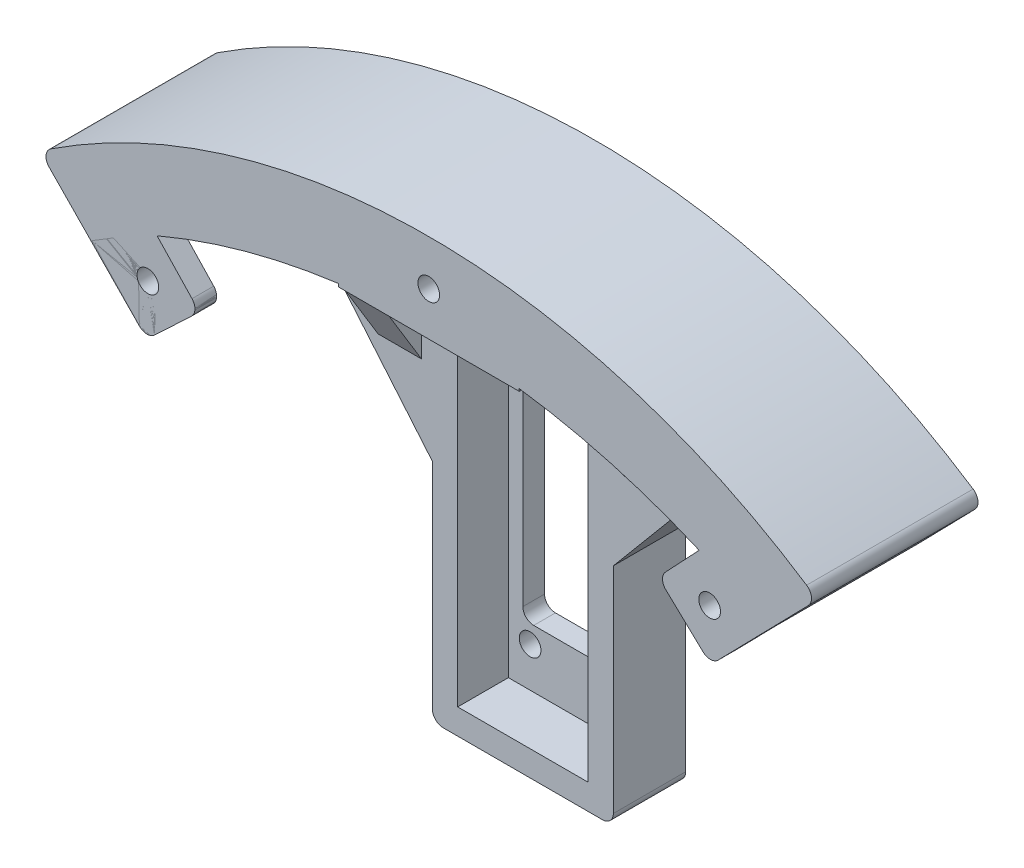
SolidWorks part; units mm, degrees
material "ABS"
ref_plane "Alzado" through (0, 0, 0) normal (0, 0, 1) x (1, 0, 0)
ref_plane "Planta" through (0, 0, 0) normal (0, 1, 0) x (1, 0, 0)
ref_plane "Vista lateral" through (0, 0, 0) normal (1, 0, 0) x (0, 0, -1)
sketch "Croquis1" plane through (0, 0, 0) normal (0, 0, 1) x (1, 0, 0)
  circle A0 centre (0, 0) radius 100
  dimension "D1" = 200
extrude "Saliente-Extruir1" add sketch "Croquis1" along normal blind 3
sketch "Croquis3" plane through (0, 0, 3) normal (0, 0, 1) x (1, 0, 0)
  line L0 (0, 0) -> (190, 0) construction
  circle A0 centre (190, 0) radius 110
  dimension "D1" = 220
  dimension "D2" = 190
extrude "Cortar-Extruir1" cut sketch "Croquis3" against normal blind 3
fillet "Redondeo1" radius 10 2 edges at (89.4737, -44.6594, 1.5) (89.4737, 44.6594, 1.5)
sketch "Croquis5" plane through (0, 0, 3) normal (0, 0, 1) x (1, 0, 0)
  line L0 (0, -100) -> (0, 100) construction
  line L1 (-100, 0) -> (80, 0) construction
  line L2 (0, 0) -> (-70.7107, -70.7107) construction
  line L3 (-70.7107, -70.7107) -> (70.7107, 70.7107) construction
  line L4 (0, 0) -> (-70.7107, 70.7107) construction
  line L5 (-70.7107, 70.7107) -> (70.7107, -70.7107) construction
  line L6 (-70.7107, -70.7107) -> (-58.3363, -83.085) construction
  line L9 (-58.3363, -83.085) -> (-83.085, -58.3363)
  line L11 (-83.085, -58.3363) -> (-65.4074, -40.6586)
  line L12 (-65.4074, -40.6586) -> (-40.6586, -65.4074)
  line L13 (-40.6586, -65.4074) -> (-58.3363, -83.085)
  line L14 (-70.7107, 70.7107) -> (-83.085, 58.3363) construction
  line L15 (-83.085, 58.3363) -> (-100, 0) construction
  line L17 (-83.085, 58.3363) -> (-58.3363, 83.085)
  line L18 (-58.3363, 83.085) -> (-40.6586, 65.4074)
  line L19 (-40.6586, 65.4074) -> (-65.4074, 40.6586)
  line L20 (-65.4074, 40.6586) -> (-83.085, 58.3363)
  line L22 (70.7107, -70.7107) -> (58.3363, -83.085) construction
  line L23 (58.3363, -83.085) -> (0, -100) construction
  line L24 (58.3363, -83.085) -> (83.085, -58.3363)
  line L25 (83.085, -58.3363) -> (65.4074, -40.6586)
  line L26 (65.4074, -40.6586) -> (40.6586, -65.4074)
  line L27 (40.6586, -65.4074) -> (58.3363, -83.085)
  line L28 (70.7107, 70.7107) -> (58.3363, 83.085) construction
  line L29 (58.3363, 83.085) -> (0, 100) construction
  line L30 (58.3363, 83.085) -> (83.085, 58.3363)
  line L31 (83.085, 58.3363) -> (65.4074, 40.6586)
  line L32 (65.4074, 40.6586) -> (40.6586, 65.4074)
  line L33 (40.6586, 65.4074) -> (58.3363, 83.085)
  arc A0 (87.1345, 49.0671) -> (87.1345, -49.0671) centre (0, 0) ccw construction
  arc A1 (87.7193, 40.4803) -> (87.7193, -40.4803) centre (190, 0) ccw construction
  point P36 (0, 0)
  dimension "D2" = 17.5
  dimension "D3" = 25
  dimension "D4" = 35
  dimension "D5" = 25
  dimension "D6" = 35
  dimension "D8" = 25
  dimension "D9" = 17.5
  dimension "D7" = 35
  dimension "D10" = 90
  dimension "D11" = 17.5
  dimension "D12" = 17.5
  dimension "D13" = 35
  dimension "D14" = 25
  dimension "D15" = 134.3503
  dimension "D16" = 100
extrude "Cortar-Extruir6" cut sketch "Croquis5" against normal blind 10
sketch "Croquis12" plane through (0, 0, 3) normal (0, 0, 1) x (1, 0, 0)
  line L0 (-53.033, -53.033) -> (-39.9421, -50.0116) construction
  line L1 (-40.6586, -65.4074) -> (-65.4074, -40.6586) construction
  line L2 (-39.9421, -50.0116) -> (-36.8049, -63.6043) construction
  line L3 (-36.8049, -63.6043) -> (-63.6043, -36.8049) construction
  line L4 (-63.6043, -36.8049) -> (-47.6661, -20.8667) construction
  line L6 (53.033, -53.033) -> (-53.033, 53.033) construction
  line L7 (65.4074, -40.6586) -> (40.6586, -65.4074) construction
  line L8 (-65.4074, 40.6586) -> (-40.6586, 65.4074) construction
  line L9 (36.8049, 63.6043) -> (20.8667, 47.6661) construction
  line L10 (63.6043, 36.8049) -> (36.8049, 63.6043) construction
  line L11 (50.0116, 39.9421) -> (63.6043, 36.8049) construction
  line L12 (53.033, 53.033) -> (50.0116, 39.9421) construction
  line L14 (53.033, -53.033) -> (50.2046, -50.2046) construction
  line L15 (50.2046, -50.2046) -> (36.8049, -63.6043) construction
  line L16 (36.8049, -63.6043) -> (63.6043, -36.8049) construction
  line L17 (63.6043, -36.8049) -> (47.6661, -20.8667) construction
  line L19 (-53.033, -53.033) -> (53.033, 53.033) construction
  line L20 (-36.8049, 63.6043) -> (-20.8667, 47.6661) construction
  line L21 (-63.6043, 36.8049) -> (-36.8049, 63.6043) construction
  line L22 (-50.2046, 50.2046) -> (-63.6043, 36.8049) construction
  line L23 (-53.033, 53.033) -> (-50.2046, 50.2046) construction
  circle A0 centre (-63.6043, -36.8049) radius 1.5
  circle A1 centre (-36.8049, -63.6043) radius 1.5
  circle A2 centre (-47.6661, -20.8667) radius 1.5
  circle A3 centre (-20.8667, -47.6661) radius 1.5
  circle A5 centre (47.6661, 20.8667) radius 1.5
  circle A6 centre (20.8667, 47.6661) radius 1.5
  circle A7 centre (63.6043, 36.8049) radius 1.5
  circle A8 centre (36.8049, 63.6043) radius 1.5
  circle A10 centre (20.8667, -47.6661) radius 1.5
  circle A11 centre (47.6661, -20.8667) radius 1.5
  circle A12 centre (63.6043, -36.8049) radius 1.5
  circle A13 centre (36.8049, -63.6043) radius 1.5
  circle A15 centre (-63.6043, 36.8049) radius 1.5
  circle A16 centre (-36.8049, 63.6043) radius 1.5
  circle A17 centre (-20.8667, 47.6661) radius 1.5
  circle A18 centre (-47.6661, 20.8667) radius 1.5
  dimension "D2" = 3
  dimension "D3" = 3
  dimension "D4" = 4
  dimension "D5" = 4
  dimension "D6" = 3
  dimension "D7" = 3
  dimension "D8" = 37.9
  dimension "D9" = 22.54
  dimension "D10" = 22.54
  dimension "D11" = 37.9
  dimension "D12" = 18.95
  dimension "D13" = 18.95
  dimension "D14" = 3
  dimension "D15" = 3
  dimension "D16" = 3
  dimension "D17" = 3
  dimension "D18" = 37.9
  dimension "D19" = 22.54
  dimension "D20" = 22.54
  dimension "D21" = 37.9
  dimension "D22" = 4
  dimension "D1" = 13.95
extrude "Cortar-Extruir7" cut sketch "Croquis12" against normal through all
sketch "Croquis9" plane through (0, 0, 3) normal (0, 0, 1) x (1, 0, 0)
  line L0 (0, 0) -> (-100, 0) construction
  line L5 (0, 100) -> (0, -100) construction
  line L6 (38.9591, 4) -> (43.4591, 4)
  line L7 (38.9591, 4) -> (38.9591, -4)
  line L8 (38.9591, -4) -> (43.4591, -4)
  line L9 (43.4591, 4) -> (43.4591, -4)
  line L10 (-4, -52) -> (4, -52)
  line L11 (-58.1901, 4) -> (-62.6901, 4)
  line L12 (-58.1901, 4) -> (-58.1901, -4)
  line L13 (-58.1901, -4) -> (-62.6901, -4)
  line L14 (-62.6901, 4) -> (-62.6901, -4)
  line L15 (-4, 56.5) -> (4, 56.5)
  line L16 (-4, 56.5) -> (-4, 52)
  line L17 (-4, 52) -> (4, 52)
  line L18 (4, 56.5) -> (4, 52)
  line L19 (4, -56.5) -> (4, -52)
  line L20 (-4, -56.5) -> (4, -56.5)
  line L21 (-4, -56.5) -> (-4, -52)
  line L22 (0, 0) -> (80, 0) construction
  line L24 (-58.2511, -4) -> (-58.2738, -4) construction
  circle A0 centre (71.9, -4) radius 1.5
  circle A1 centre (35.9591, 4) radius 1.5
  circle A4 centre (71.9591, 4) radius 1.5
  circle A5 centre (35.9, -4) radius 1.5
  arc A6 (-81.9939, 57.2451) -> (-81.9939, -57.2451) centre (0, 0) ccw construction
  arc A7 (87.7193, 40.4803) -> (87.7193, -40.4803) centre (190, 0) ccw construction
  circle A8 centre (-91.1901, 4) radius 1.5
  circle A9 centre (-91.1901, -4) radius 1.5
  circle A10 centre (-55.1901, 4) radius 1.5
  circle A11 centre (-55.1901, -4) radius 1.5
  circle A12 centre (-4, 85) radius 1.5
  circle A13 centre (4, 85) radius 1.5
  circle A14 centre (-4, 49) radius 1.5
  circle A15 centre (4, 49) radius 1.5
  circle A20 centre (-4, -49) radius 1.5
  circle A21 centre (4, -49) radius 1.5
  circle A22 centre (4, -85) radius 1.5
  circle A23 centre (-4, -85) radius 1.5
  arc A24 (87.1345, 49.0671) -> (81.9939, 57.2451) centre (0, 0) ccw construction
  arc A25 (57.2451, 81.9939) -> (-57.2451, 81.9939) centre (0, 0) ccw construction
  dimension "D6" = 35.9
  dimension "D7" = 3
  dimension "D8" = 36
  dimension "D9" = 36
  dimension "D10" = 3
  dimension "D11" = 3
  dimension "D12" = 4
  dimension "D13" = 4
  dimension "D14" = 3
  dimension "D15" = 3
  dimension "D16" = 3
  dimension "D21" = 4
  dimension "D22" = 4
  dimension "D23" = 3
  dimension "D24" = 3
  dimension "D25" = 4
  dimension "D26" = 4
  dimension "D27" = 36
  dimension "D28" = 36
  dimension "D29" = 91.1901
  dimension "D30" = 91.1901
  dimension "D35" = 3
  dimension "D36" = 3
  dimension "D37" = 8
  dimension "D38" = 4
  dimension "D39" = 3
  dimension "D40" = 3
  dimension "D41" = 8
  dimension "D42" = 36
  dimension "D43" = 36
  dimension "D44" = 36
  dimension "D45" = 4
  dimension "D46" = 4
  dimension "D51" = 4
  dimension "D52" = 4
  dimension "D53" = 36.1809
  dimension "D55" = 36
  dimension "D56" = 49
  dimension "D57" = 49
  dimension "D58" = 3
  dimension "D59" = 3
  dimension "D60" = 3
  dimension "D61" = 3
  dimension "D62" = 4.5
  dimension "D32" = 8
  dimension "D64" = 0
  dimension "D69" = 8
  dimension "D70" = 4
  dimension "D71" = 85.0941
  dimension "D72" = 85.0941
  dimension "D17" = 4.5
  dimension "D18" = 8
  dimension "D19" = 3
  dimension "D20" = 0
  dimension "D31" = 3.061
  dimension "D33" = 3
  dimension "D34" = 0
  dimension "D47" = 8
  dimension "D48" = 4.5
  dimension "D49" = 0
  dimension "D50" = 3
  dimension "D54" = 4
  dimension "D63" = 0
  dimension "D65" = 3
  dimension "D66" = 4.5
  dimension "D67" = 8
  dimension "D68" = 3
extrude "Cortar-Extruir5" cut sketch "Croquis9" against normal blind 10
sketch "Croquis13" plane through (0, 0, 3) normal (0, 0, 1) x (1, 0, 0)
  line L0 (-57.2451, 81.9939) -> (-46.4963, 71.2451) construction
  line L1 (-40.6586, 65.4074) -> (-57.2451, 81.9939) construction
  line L2 (57.2451, 81.9939) -> (46.2825, 71.0313) construction
  line L3 (57.2451, 81.9939) -> (40.6586, 65.4074) construction
  line L4 (0, 100) -> (0, 95) construction
  line L5 (-46.4963, 71.2451) -> (-40.6586, 65.4074)
  line L6 (-40.6586, 65.4074) -> (-65.4074, 40.6586)
  line L7 (-65.4074, 40.6586) -> (-81.9939, 57.2451)
  line L8 (-81.9939, -57.2451) -> (-65.4074, -40.6586)
  line L9 (-65.4074, -40.6586) -> (-40.6586, -65.4074)
  line L10 (-40.6586, -65.4074) -> (-57.2451, -81.9939)
  line L12 (81.9939, -57.2451) -> (65.4074, -40.6586)
  line L13 (65.4074, -40.6586) -> (40.6586, -65.4074)
  line L14 (40.6586, -65.4074) -> (57.2451, -81.9939)
  line L15 (46.2825, 71.0313) -> (40.6586, 65.4074)
  line L16 (40.6586, 65.4074) -> (65.4074, 40.6586)
  line L17 (65.4074, 40.6586) -> (81.9939, 57.2451)
  arc A0 (57.2451, 81.9939) -> (-57.2451, 81.9939) centre (0, 0) ccw construction
  arc A1 (-46.4963, 71.2451) -> (46.2825, 71.0313) centre (-0.2711, -0.0867) cw
  arc A2 (-81.9939, 57.2451) -> (-81.9939, -57.2451) centre (0, 0) ccw
  arc A3 (-57.2451, -81.9939) -> (57.2451, -81.9939) centre (0, 0) ccw
  arc A4 (87.7193, -40.4803) -> (87.7193, 40.4803) centre (190, 0) cw
  arc A7 (81.9939, -57.2451) -> (87.7193, -40.4803) centre (81.3824, -47.6762) ccw
  arc A8 (81.9939, 57.2451) -> (87.7193, 40.4803) centre (84.8566, 48.8627) cw
  dimension "D2" = 85
  dimension "D3" = 100
  dimension "D4" = 110
  dimension "D5" = 100
  dimension "D6" = 0.2846
  dimension "D7" = 17.753
  dimension "D1" = 5
extrude "Cortar-Extruir9" cut sketch "Croquis13" against normal through all
sketch "Croquis14" plane through (0, 0, 0) normal (0, 0, -1) x (-1, 0, 0)
  line L1 (38.9455, 63.246) -> (31.6736, 70.1104)
  line L6 (38.9455, 63.246) -> (46.4963, 71.2451)
  line L7 (31.6736, 70.1104) -> (37.5285, 76.3128)
  line L10 (0, 100) -> (0, 0) construction
  line L11 (-38.9455, 63.246) -> (-31.6736, 70.1104)
  line L12 (-31.6736, 70.1104) -> (-37.5285, 76.3128)
  line L13 (-38.9455, 63.246) -> (-46.4963, 71.2451)
  arc A3 (-5.4734, 84.719) -> (-46.2825, 71.0313) centre (0.2711, -0.0867) ccw construction
  arc A4 (46.4963, 71.2451) -> (37.5285, 76.3128) centre (-4.6568, -8.8071) ccw
  arc A6 (57.2451, 81.9939) -> (-57.2451, 81.9939) centre (0, 0) ccw construction
  arc A7 (-46.4963, 71.2451) -> (-37.5285, 76.3128) centre (4.6568, -8.8071) cw
  dimension "D8" = 95
  dimension "D2" = 10
  dimension "D5" = 8.5293
  dimension "D7" = 11
extrude "Saliente-Extruir3" add sketch "Croquis14" against normal blind 3
sketch "Croquis15" plane through (0, 0, 3) normal (0, 0, 1) x (1, 0, 0)
  line L0 (57.2451, 81.9939) -> (38.9455, 63.246)
  line L1 (38.9455, 63.246) -> (31.6736, 70.1104)
  line L2 (31.6736, 70.1104) -> (37.3569, 76.131)
  line L3 (-37.5285, 76.3128) -> (-31.6736, 70.1104)
  line L4 (-31.6736, 70.1104) -> (-38.9455, 63.246)
  line L5 (-38.9455, 63.246) -> (-57.2451, 81.9939)
  line L8 (0, 100) -> (0, 97.5) construction
  arc A0 (57.2451, 81.9939) -> (-57.2451, 81.9939) centre (0, 0) ccw
  arc A1 (37.3569, 76.131) -> (-37.5285, 76.3128) centre (-0.2978, -11.0878) ccw
  dimension "D1" = 100
  dimension "D2" = 95
  dimension "D3" = 2.5
extrude "Saliente-Extruir4" add sketch "Croquis15" against normal blind 23
sketch "Croquis23" plane through (0, 0, -20) normal (0, 0, -1) x (-1, 0, 0)
  line L0 (0, 100) -> (0, 70) construction
  line L2 (-12.5, 24.2157) -> (12.5, 24.2157)
  line L3 (-12.5, 24.2157) -> (-12.5, 99.2157)
  line L4 (-12.5, 99.2157) -> (12.5, 99.2157)
  line L5 (12.5, 24.2157) -> (12.5, 99.2157)
  arc A1 (57.2451, 81.9939) -> (-57.2451, 81.9939) centre (0, 0) ccw construction
  arc A2 (57.2451, 81.9939) -> (-57.2451, 81.9939) centre (0, 0) ccw construction
  point P13 (0, 100)
  dimension "D1" = 30
  dimension "D2" = 25
  dimension "D3" = 12.5
  dimension "D4" = 75
extrude "Saliente-Extruir5" add sketch "Croquis23" against normal through all
sketch "Croquis24" plane through (0, 24.2157, 0) normal (0, -1, 0) x (1, 0, 0)
  line L0 (12.5, 3) -> (12.5, -20) construction
  line L1 (-12.5, 3) -> (12.5, 3)
  line L2 (-12.5, 3) -> (-12.5, -10)
  line L3 (-12.5, -10) -> (12.5, -10)
  line L4 (12.5, 3) -> (12.5, -10)
  dimension "D1" = 13
extrude "Cortar-Extruir10" cut sketch "Croquis24" against normal blind 58.5
sketch "Croquis26" plane through (0, 0, -20) normal (0, 0, -1) x (-1, 0, 0)
  line L0 (-37.3569, 76.131) -> (-31.6736, 70.1104)
  line L1 (-37.3569, 76.131) -> (-44.7294, 69.1716)
  line L2 (-31.6736, 70.1104) -> (-38.9455, 63.246)
  line L3 (-44.7294, 69.1716) -> (-38.9455, 63.246)
  line L5 (-38.9455, 63.246) -> (-57.2451, 81.9939) construction
  line L6 (0, 100) -> (0, 24.2157) construction
  line L7 (-12.5, 24.2157) -> (12.5, 24.2157) construction
  line L8 (31.6736, 70.1104) -> (38.9455, 63.246)
  line L9 (37.3569, 76.131) -> (31.6736, 70.1104)
  line L10 (37.3569, 76.131) -> (44.7294, 69.1716)
  line L11 (44.7294, 69.1716) -> (38.9455, 63.246)
  arc A0 (57.2451, 81.9939) -> (-57.2451, 81.9939) centre (0, 0) ccw construction
extrude "Cortar-Extruir11" cut sketch "Croquis26" against normal blind 20
sketch "Croquis27" plane through (0, 0, -10) normal (0, 0, 1) x (1, 0, 0)
  line L0 (-12.5, 82.7157) -> (-12.5, 24.2157) construction
  line L1 (-9, 79.2157) -> (9, 79.2157)
  line L2 (-9, 79.2157) -> (-9, 27.7157)
  line L3 (-9, 27.7157) -> (9, 27.7157)
  line L4 (9, 79.2157) -> (9, 27.7157)
  line L5 (12.5, 82.7157) -> (12.5, 24.2157) construction
  line L6 (-12.5, 24.2157) -> (12.5, 24.2157) construction
  line L7 (12.5, 82.7157) -> (-12.5, 82.7157) construction
  dimension "D1" = 3.5
  dimension "D2" = 3.5
  dimension "D3" = 3.5
  dimension "D4" = 3.5
extrude "Cortar-Extruir12" cut sketch "Croquis27" against normal blind 7
sketch "Croquis28" plane through (0, 0, -17) normal (0, 0, 1) x (1, 0, 0)
  line L1 (9, 79.2157) -> (-9, 79.2157) construction
  line L2 (9, 79.2157) -> (-9, 79.2157) construction
  line L9 (9, 27.7157) -> (9, 79.2157) construction
  line L10 (-9, 79.2157) -> (-9, 27.7157) construction
  line L12 (-7, 72.7157) -> (7, 72.7157)
  line L13 (-7, 72.7157) -> (-7, 35.7157)
  line L14 (-7, 35.7157) -> (7, 35.7157)
  line L15 (7, 72.7157) -> (7, 35.7157)
  circle A0 centre (-6, 75.2157) radius 1.5
  circle A1 centre (6, 75.2157) radius 1.5
  circle A2 centre (-6, 33.2157) radius 1.5
  circle A3 centre (6, 33.2157) radius 1.5
  dimension "D1" = 3
  dimension "D2" = 3
  dimension "D3" = 12
  dimension "D4" = 3
  dimension "D5" = 3
  dimension "D6" = 12
  dimension "D7" = 42
  dimension "D8" = 42
  dimension "D9" = 3
  dimension "D10" = 4
  dimension "D11" = 4
  dimension "D12" = 3
  dimension "D13" = 37
  dimension "D14" = 2.5
  dimension "D15" = 2
  dimension "D16" = 2
extrude "Cortar-Extruir13" cut sketch "Croquis28" against normal blind 7
sketch "Croquis30" plane through (0, 0, 3) normal (0, 0, 1) x (1, 0, 0)
  line L0 (-38.9455, 63.246) -> (-31.6736, 70.1104) construction
  line L1 (-57.2451, 81.9939) -> (-38.9455, 63.246) construction
  line L2 (38.9455, 63.246) -> (57.2451, 81.9939) construction
  line L3 (38.9455, 63.246) -> (31.6736, 70.1104) construction
  line L4 (12.5, 82.7157) -> (-12.5, 82.7157) construction
  line L6 (-12.5, 82.7157) -> (-12.5, 99.2157) construction
  circle A0 centre (-38.801, 70.2561) radius 1.5
  circle A1 centre (38.8021, 70.2572) radius 1.5
  circle A2 centre (0, 88.7157) radius 1.5
  dimension "D1" = 3
  dimension "D2" = 4.9985
  dimension "D3" = 5
  dimension "D4" = 3
  dimension "D5" = 5
  dimension "D6" = 5
  dimension "D7" = 3
  dimension "D8" = 6
  dimension "D9" = 12.5
extrude "Cortar-Extruir14" cut sketch "Croquis30" against normal blind 5
fillet "Redondeo2" radius 1.5 6 edges at (-12.5, 24.2157, -15) (12.5, 24.2157, -15) (7, 35.7157, -18.5) (-7, 35.7157, -18.5) (7, 72.7157, -18.5) (-7, 72.7157, -18.5)
fillet "Redondeo3" radius 1.5 6 edges at (-57.2451, 81.9939, -8.5) (57.2451, 81.9939, -8.5) (31.6736, 70.1104, 1.5) (38.9455, 63.246, 1.5) (-31.6736, 70.1104, 1.5) (-38.9455, 63.246, 1.5)
fillet "Redondeo4" radius 1.5 2 edges at (-31.6736, 70.1104, 1.5) (-38.9455, 63.246, 1.5)
sketch "Croquis33" plane through (0, 0, 3) normal (0, 0, 1) x (1, 0, 0)
  circle A0 centre (0, 0) radius 100
  circle A1 centre (0, 0) radius 95
  dimension "D1" = 200
  dimension "D2" = 190
extrude "Cortar-Extruir15" cut sketch "Croquis33" against normal through all
fillet "Redondeo5" radius 1.5 2 edges at (53.7027, 78.3647, -8.5) (-53.7027, 78.3647, -8.5)
sketch "Croquis36" plane through (0, 0, -20) normal (0, 0, -1) x (-1, 0, 0)
  line L0 (-12.5, 55.35) -> (-31.7836, 78.3313)
  line L2 (-12.5, 94.174) -> (-12.5, 25.7157) construction
  line L3 (-12.5, 55.35) -> (-12.5, 85.35)
  line L4 (-31.7836, 78.3313) -> (-12.5, 85.35)
  line L5 (0, 95) -> (0, 24.2157) construction
  line L6 (-11, 24.2157) -> (11, 24.2157) construction
  line L7 (12.5, 55.35) -> (31.7836, 78.3313)
  line L8 (12.5, 55.35) -> (12.5, 85.35)
  line L9 (31.7836, 78.3313) -> (12.5, 85.35)
  arc A1 (37.5285, 76.3128) -> (-37.3569, 76.131) centre (0.2978, -11.0878) ccw construction
  arc A2 (52.1952, 79.3767) -> (-52.1952, 79.3767) centre (0, 0) ccw construction
  dimension "D1" = 30
  dimension "D2" = 40
  dimension "D3" = 30
extrude "Saliente-Extruir6" add sketch "Croquis36" against normal blind 10
ref_plane "Plano1" through (20, 0, 0) normal (1, 0, 0) x (0, 0, -1)
sketch "Croquis37" plane through (20, 0, 0) normal (1, 0, 0) x (0, 0, -1)
  line L0 (10, 66.8406) -> (-3, 88.1948)
  line L1 (10, 78.3313) -> (10, 55.35) construction
  line L2 (-3, 83.0462) -> (-3, 76.131) construction
  line L3 (10, 66.8406) -> (10, 88.1948)
  line L4 (10, 88.1948) -> (-3, 88.1948)
  dimension "D1" = 25
extrude "Saliente-Extruir7" add sketch "Croquis37" against normal blind 6
mirror "Simetría1" about plane through (0, 0, 0) normal (1, 0, 0) of "Saliente-Extruir7"
